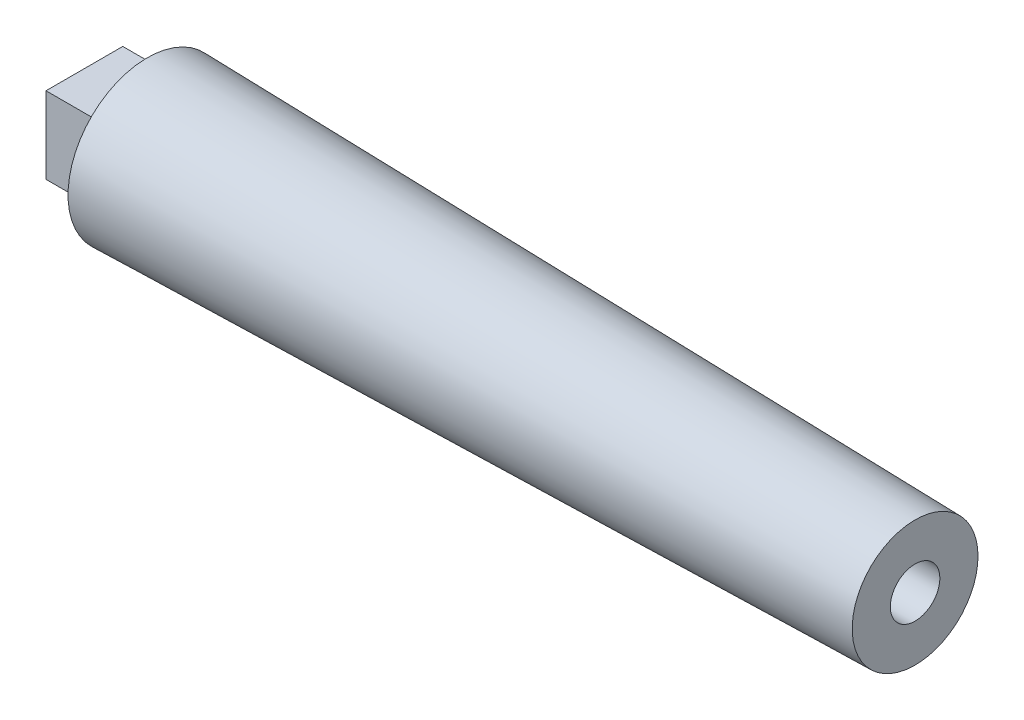
SolidWorks part; units mm, degrees
ref_plane "Front Plane" through (0, 0, 0) normal (0, 0, 1) x (1, 0, 0)
ref_plane "Top Plane" through (0, 0, 0) normal (0, 1, 0) x (1, 0, 0)
ref_plane "Right Plane" through (0, 0, 0) normal (1, 0, 0) x (0, 0, -1)
sketch "Sketch1" plane through (0, 0, 0) normal (0, 0, 1) x (1, 0, 0)
  line L0 (0, 0) -> (0, 16)
  line L1 (0, 16) -> (155, 12.7)
  line L2 (155, 12.7) -> (155, 0)
  line L3 (155, 0) -> (0, 0)
  dimension "D1" = 155
  dimension "D2" = 12.7
  dimension "D3" = 16
revolve "Revolve1" add sketch "Sketch1" angle 360 about L3
sketch "Sketch2" plane through (0, 0, 0) normal (-1, 0, 0) x (0, 0, 1)
  line L1 (-7.75, 7.75) -> (7.75, 7.75)
  line L2 (-7.75, 7.75) -> (-7.75, -7.75)
  line L3 (-7.75, -7.75) -> (7.75, -7.75)
  line L4 (7.75, 7.75) -> (7.75, -7.75)
  line L5 (-7.75, 7.75) -> (7.75, -7.75) construction
  line L6 (-7.75, -7.75) -> (7.75, 7.75) construction
  point P0 (0, 0)
  dimension "D1" = 15.5
extrude "Boss-Extrude1" add sketch "Sketch2" along normal blind 12.7
sketch "Sketch3" plane through (155, 0, 0) normal (1, 0, 0) x (0, 0, -1)
  circle A0 centre (0, 0) radius 5
  dimension "D1" = 10
extrude "Cut-Extrude1" cut sketch "Sketch3" against normal blind 26
